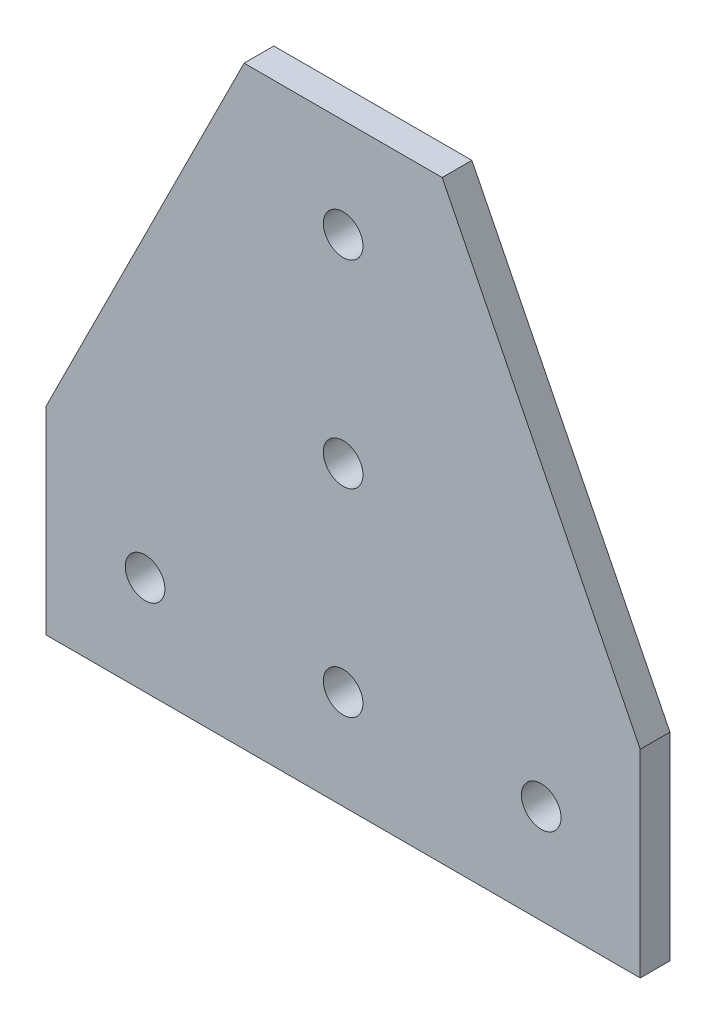
SolidWorks part; units mm, degrees
ref_plane "前视基准面" through (0, 0, 0) normal (0, 0, 1) x (1, 0, 0)
ref_plane "上视基准面" through (0, 0, 0) normal (0, 1, 0) x (1, 0, 0)
ref_plane "右视基准面" through (0, 0, 0) normal (1, 0, 0) x (0, 0, -1)
sketch "草图1" plane through (0, 0, 0) normal (0, 0, 1) x (1, 0, 0)
  line L0 (1.346, -83.3662) -> (61.346, -83.3662)
  line L1 (61.346, -83.3662) -> (61.346, -63.3662)
  line L2 (61.346, -63.3662) -> (41.346, -23.3662)
  line L3 (41.346, -23.3662) -> (21.346, -23.3662)
  line L4 (21.346, -23.3662) -> (1.346, -63.3662)
  line L5 (1.346, -63.3662) -> (1.346, -83.3662)
  circle A0 centre (31.346, -33.3662) radius 2
  circle A1 centre (31.346, -53.3662) radius 2
  circle A2 centre (11.346, -73.3662) radius 2
  circle A3 centre (31.346, -73.3662) radius 2
  circle A4 centre (51.346, -73.3662) radius 2
extrude "凸台-拉伸1" add sketch "草图1" along normal blind 3
